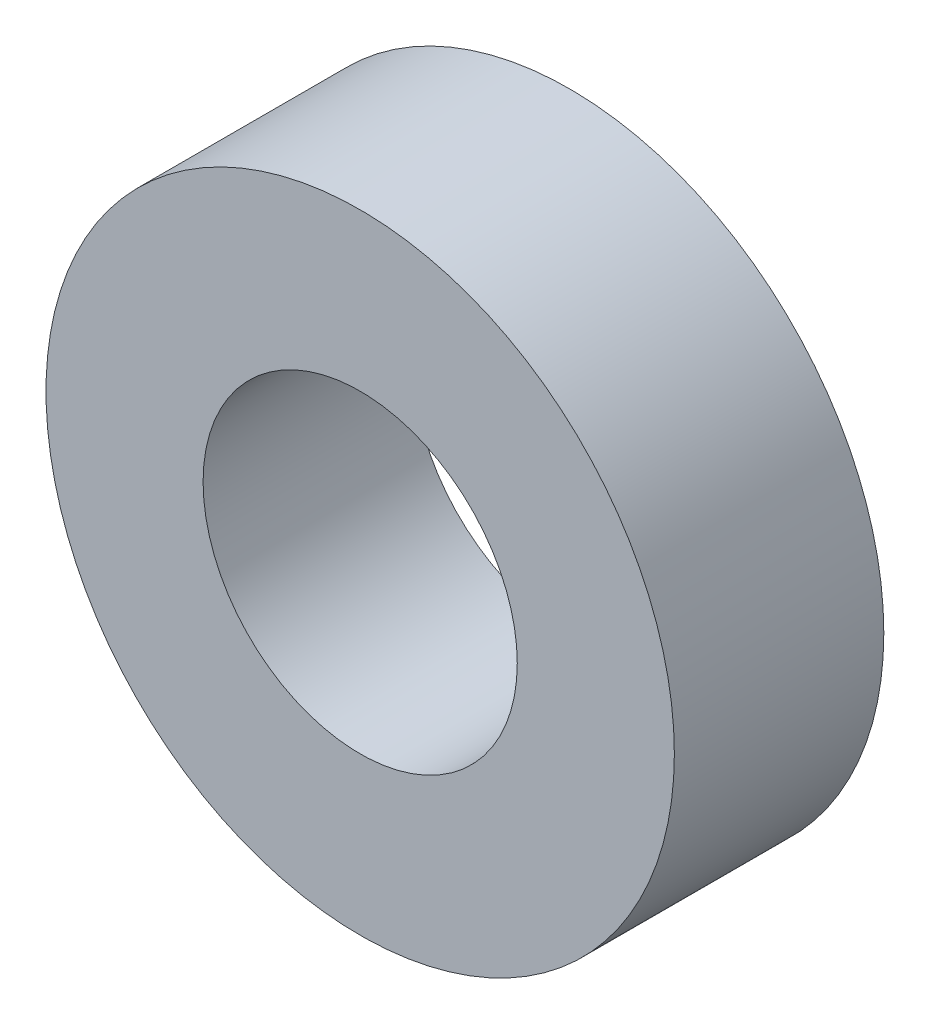
SolidWorks part; units mm, degrees
material "Pine"
ref_plane "Front Plane" through (0, 0, 0) normal (0, 0, 1) x (1, 0, 0)
ref_plane "Top Plane" through (0, 0, 0) normal (0, 1, 0) x (1, 0, 0)
ref_plane "Right Plane" through (0, 0, 0) normal (1, 0, 0) x (0, 0, -1)
other "Configuration Table"
sketch "Sketch1" plane through (0, 0, 0) normal (0, 0, 1) x (1, 0, 0)
  circle A0 centre (0, 0) radius 25.4
  circle A1 centre (0, 0) radius 9.525
  dimension "D1" = 50.8
  dimension "D2" = 19.05
extrude "Boss-Extrude1" [suppressed] add sketch "Sketch1" along normal blind 50.8
sketch "Sketch2" plane through (0, 0, 0) normal (0, 0, 1) x (1, 0, 0)
  circle A2 centre (0, 0) radius 6.35
  circle A3 centre (0, 0) radius 25.4
  dimension "D1" = 12.7
  dimension "D2" = 50.8
extrude "Boss-Extrude2" [suppressed] add sketch "Sketch2" along normal blind 25.4
sketch "Sketch4" plane through (0, 0, 0) normal (0, 1, 0) x (1, 0, 0)
  line L0 (0, 0) -> (0, -35.0188) construction
  line L6 (-19.05, 0) -> (-9.525, 0)
  line L7 (-19.05, 0) -> (-19.05, -25.4)
  line L8 (-19.05, -25.4) -> (-9.525, -25.4)
  line L9 (-9.525, 0) -> (-9.525, -25.4)
  dimension "D1" = 25.4
  dimension "D2" = 38.1
  dimension "D3" = 19.05
revolve "Revolve2" [suppressed] add sketch "Sketch4" angle 360 about L0
sketch "Sketch5" plane through (0, 0, 0) normal (0, 0, 1) x (1, 0, 0)
  circle A0 centre (0, 0) radius 9.525
  circle A1 centre (0, 0) radius 19.05
  dimension "D1" = 19.05
  dimension "D2" = 38.1
extrude "Boss-Extrude3" add sketch "Sketch5" along normal blind 12.7
sketch "Sketch7" [suppressed] plane through (0, 0, 0) normal (1, 0, 0) x (0, 0, -1)
  line L0 (0, 0) -> (-69.6482, 0) construction
  line L2 (-28.575, -25.5225) -> (-22.225, -25.5225)
  line L3 (-28.575, -25.5225) -> (-28.575, -21.5601)
  line L4 (-28.575, -21.5601) -> (-22.225, -21.5601)
  line L5 (-22.225, -25.5225) -> (-22.225, -21.5601)
  point P9 (-25.4, -25.5225)
  dimension "D1" = 3.9624
  dimension "D2" = 6.35
  dimension "D3" = 25.4
revolve "Cut-Revolve1" [suppressed] cut sketch "Sketch7" angle 360 about L0
sketch "Sketch8" [suppressed] plane through (0, 0, 0) normal (0, 1, 0) x (1, 0, 0)
  line L0 (0, 0) -> (0, -14.4938) construction
  line L1 (-19.05, 0) -> (-9.525, 0)
  line L2 (-9.525, 0) -> (-9.525, -13.97)
  line L3 (-9.525, -13.97) -> (-19.05, -13.97)
  line L4 (-19.05, -13.97) -> (-19.05, 0)
  dimension "D1" = 38.1
  dimension "D2" = 19.05
  dimension "D3" = 13.97
revolve "Revolve3" [suppressed] add sketch "Sketch8" angle 360 about L0
sketch "Sketch9" [suppressed] plane through (0, 0, 13.97) normal (0, 0, 1) x (1, 0, 0)
  line L0 (0, 0) -> (19.05, 0)
  circle A0 centre (0, 0) radius 19.05 construction
sketch "Sketch10" [suppressed] plane through (0, 0, 50.8) normal (0, 0, 1) x (1, 0, 0)
  line L0 (0, 0) -> (-39.5922, 0)
